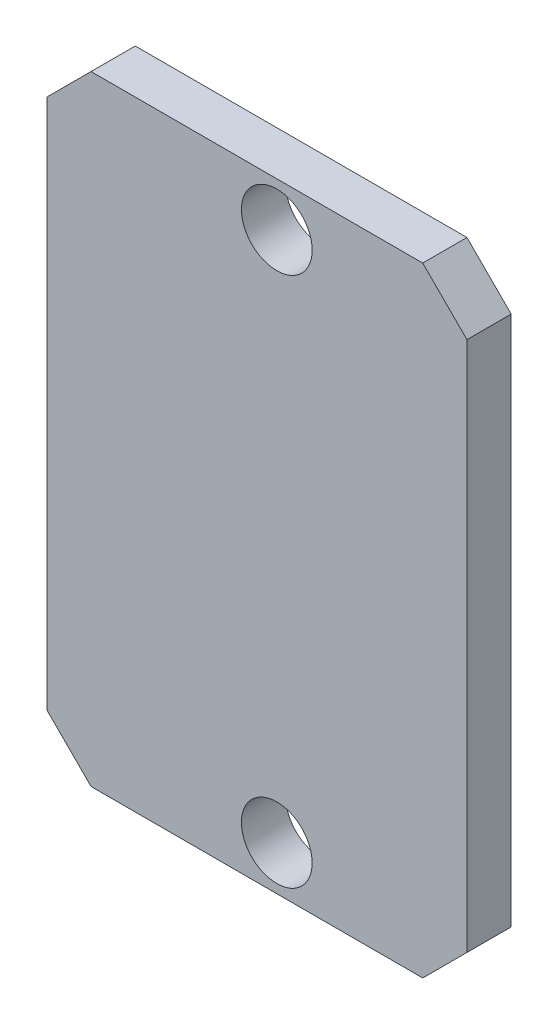
SolidWorks part; units mm, degrees
ref_plane "Front Plane" through (0, 0, 0) normal (0, 0, 1) x (1, 0, 0)
ref_plane "Top Plane" through (0, 0, 0) normal (0, 1, 0) x (1, 0, 0)
ref_plane "Right Plane" through (0, 0, 0) normal (1, 0, 0) x (0, 0, -1)
sketch "Sketch2" plane through (0, 0, 0) normal (0, 0, 1) x (1, 0, 0)
  line L0 (0, 14) -> (19, 14) construction
  line L1 (2, 0) -> (17, 0)
  line L2 (0, 2) -> (0, 26)
  line L3 (2, 28) -> (17, 28)
  line L4 (19, 2) -> (19, 26)
  line L5 (9.5, 28) -> (9.5, 0) construction
  line L6 (0, 26) -> (19, 26) construction
  line L7 (0, 2) -> (19, 2) construction
  line L8 (0, 26) -> (2, 28)
  line L9 (17, 28) -> (19, 26)
  line L10 (17, 0) -> (19, 2)
  line L11 (0, 2) -> (2, 0)
  circle A0 centre (10.4, 26) radius 1.6
  circle A3 centre (10.4, 2) radius 1.6
  point P0 (0, 0)
  point P1 (19, 28)
  point P2 (0, 28)
  point P3 (19, 0)
  dimension "D4" = 10.4
  dimension "D1" = 24
  dimension "D2" = 2
  dimension "D3" = 28
  dimension "D5" = 19
extrude "Boss-Extrude1" add sketch "Sketch2" along normal blind 2
